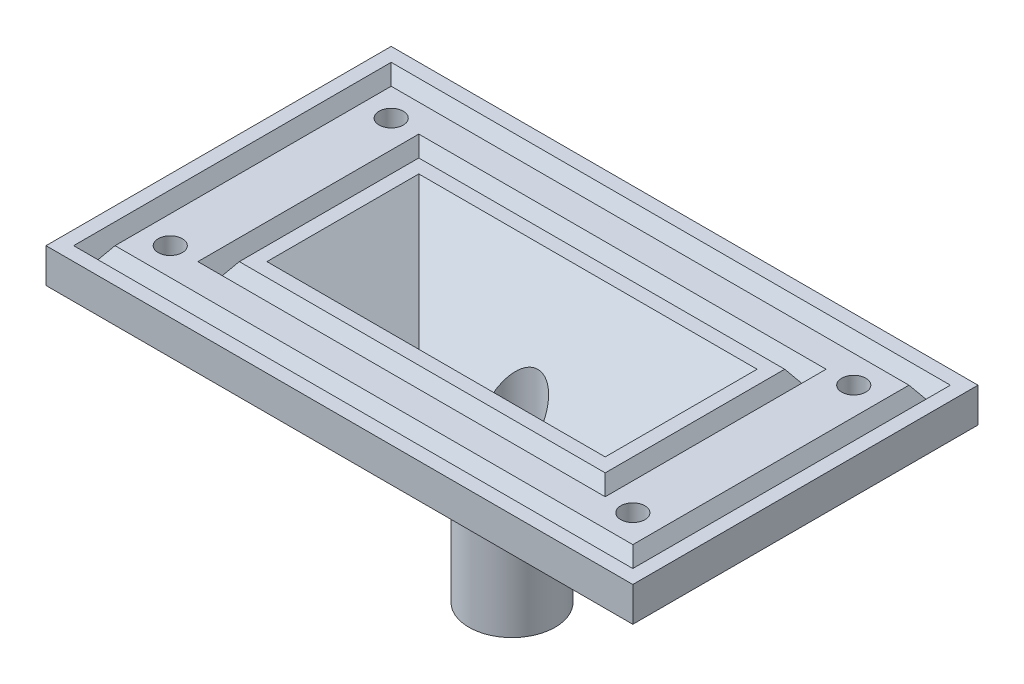
SolidWorks part; units mm, degrees
ref_plane "Front Plane" through (0, 0, 0) normal (0, 0, 1) x (1, 0, 0)
ref_plane "Top Plane" through (0, 0, 0) normal (0, 1, 0) x (1, 0, 0)
ref_plane "Right Plane" through (0, 0, 0) normal (1, 0, 0) x (0, 0, -1)
sketch "Sketch1" plane through (0, 0, 0) normal (0, 1, 0) x (1, 0, 0)
  line L1 (42.5, -25) -> (-42.5, -25)
  line L2 (42.5, -25) -> (42.5, 25)
  line L3 (42.5, 25) -> (-42.5, 25)
  line L4 (-42.5, -25) -> (-42.5, 25)
  line L5 (42.5, -25) -> (-42.5, 25) construction
  line L6 (42.5, 25) -> (-42.5, -25) construction
  point P0 (0, 0)
extrude "Base Plate" add sketch "Sketch1" along normal blind 5
sketch "Sketch4" plane through (0, 5, 0) normal (0, 1, 0) x (1, 0, 0)
  line L0 (-40.5, -23) -> (-40.5, 23)
  line L1 (-40.5, 23) -> (40.5, 23)
  line L2 (40.5, 23) -> (40.5, -23)
  line L3 (40.5, -23) -> (-40.5, -23)
  line L4 (-37.5, -20) -> (-37.5, 20)
  line L5 (-37.5, 20) -> (37.5, 20)
  line L6 (37.5, 20) -> (37.5, -20)
  line L7 (37.5, -20) -> (-37.5, -20)
  line L8 (42.5, -25) -> (42.5, 25) construction
  line L9 (-42.5, 25) -> (-42.5, -25) construction
  line L10 (-42.5, -25) -> (42.5, -25) construction
  line L11 (42.5, 25) -> (-42.5, 25) construction
  dimension "D1" = 2
  dimension "D2" = 3
  dimension "D3" = 2
  dimension "D4" = 3
  dimension "D5" = 2
  dimension "D6" = 3
  dimension "D7" = 3
  dimension "D8" = 2
extrude "Sealant Cut - Outer" cut sketch "Sketch4" against normal blind 5 draft 35
sketch "Sketch7" plane through (0, 5, 0) normal (0, 1, 0) x (1, 0, 0)
  line L0 (37.5, 20) -> (-37.5, 20) construction
  line L1 (-37.5, 20) -> (-37.5, -20) construction
  line L2 (0, 0) -> (-11.5051, 0) construction
  line L4 (0, 13.9859) -> (0, 0) construction
  circle A0 centre (-33.5, 16) radius 1.75
  circle A1 centre (-33.5, -16) radius 1.75
  circle A2 centre (33.5, -16) radius 1.75
  circle A3 centre (33.5, 16) radius 1.75
  dimension "D1" = 3.5
  dimension "D2" = 4
  dimension "D3" = 4
extrude "Scre Cut" cut sketch "Sketch7" against normal blind 5
sketch "Sketch8" plane through (0, 0, 0) normal (0, -1, 0) x (1, 0, 0)
  line L0 (0, 0) -> (0, -6.6439) construction
  line L2 (-4.9872, 0) -> (0, 0) construction
  circle A0 centre (-33.5, -16) radius 2.75
  circle A1 centre (-33.5, 16) radius 2.75
  circle A2 centre (33.5, 16) radius 2.75
  circle A3 centre (33.5, -16) radius 2.75
  dimension "D1" = 5.5
sketch "Sketch12" plane through (0, 5, 0) normal (0, 1, 0) x (1, 0, 0)
  line L0 (29.5, -16) -> (-29.5, -16)
  line L1 (-29.5, -16) -> (-29.5, 16)
  line L2 (-29.5, 16) -> (29.5, 16)
  line L3 (29.5, 16) -> (29.5, -16)
  line L4 (26.5, -13) -> (-26.5, -13)
  line L5 (-26.5, -13) -> (-26.5, 13)
  line L6 (-26.5, 13) -> (26.5, 13)
  line L7 (26.5, 13) -> (26.5, -13)
  line L8 (37.5, 20) -> (-37.5, 20) construction
  circle A0 centre (33.5, -16) radius 1.75 construction
  circle A3 centre (-33.5, 16) radius 1.75 construction
  circle A4 centre (33.5, 16) radius 1.75 construction
  dimension "D1" = 4
  dimension "D2" = 3
  dimension "D3" = 4
  dimension "D4" = 4
  dimension "D5" = 4
  dimension "D6" = 3
  dimension "D7" = 3
  dimension "D8" = 3
extrude "Sealant Cut - Inner" cut sketch "Sketch12" against normal blind 3 draft 35
sketch "Sketch13" plane through (0, 5, 0) normal (0, 1, 0) x (1, 0, 0)
  line L0 (26.5, -13) -> (26.5, 13) construction
  line L1 (-24.5, 11) -> (24.5, 11)
  line L2 (-24.5, 11) -> (-24.5, -11)
  line L3 (-24.5, -11) -> (24.5, -11)
  line L4 (24.5, 11) -> (24.5, -11)
  line L5 (-24.5, 11) -> (24.5, -11) construction
  line L6 (-24.5, -11) -> (24.5, 11) construction
  line L7 (-26.5, -13) -> (26.5, -13) construction
  point P0 (0, 0)
  dimension "D1" = 2
  dimension "D2" = 2
sketch "Sketch14" plane through (0, 0, 0) normal (0, -1, 0) x (1, 0, 0)
  line L1 (27.5, -13) -> (-27.5, -13)
  line L2 (27.5, -13) -> (27.5, 13)
  line L3 (27.5, 13) -> (-27.5, 13)
  line L4 (-27.5, -13) -> (-27.5, 13)
  line L5 (27.5, -13) -> (-27.5, 13) construction
  line L6 (27.5, 13) -> (-27.5, -13) construction
  point P0 (0, 0)
  dimension "D1" = 55
  dimension "D2" = 26
extrude "Base Block" add sketch "Sketch14" along normal blind 11
extrude "Drain" cut sketch "Sketch13" against normal blind 16 draft 40
sketch "Sketch15" plane through (0, -11, 0) normal (0, -1, 0) x (1, 0, 0)
  circle A0 centre (0, 0) radius 6.25
  dimension "D1" = 12.5
extrude "Hose connector" add sketch "Sketch15" along normal blind 20
sketch "Sketch16" plane through (0, -31, 0) normal (0, -1, 0) x (1, 0, 0)
  circle A0 centre (0, 0) radius 3.75
  circle A1 centre (0, 0) radius 6.25 construction
  dimension "D1" = 2.5
extrude "Drain Hole" cut sketch "Sketch16" against normal through all contours A0
fillet "Fillet1" radius 10 1 edges at (-27.5, -5.5, -13)
fillet "Fillet2" radius 10 1 edges at (27.5, -5.5, -13)
fillet "Fillet3" radius 10 1 edges at (27.5, -5.5, 13)
fillet "Fillet4" radius 10 1 edges at (-27.5, -5.5, 13)
extrude "Srew Heads" cut sketch "Sketch8" against normal blind 20 draft 45
